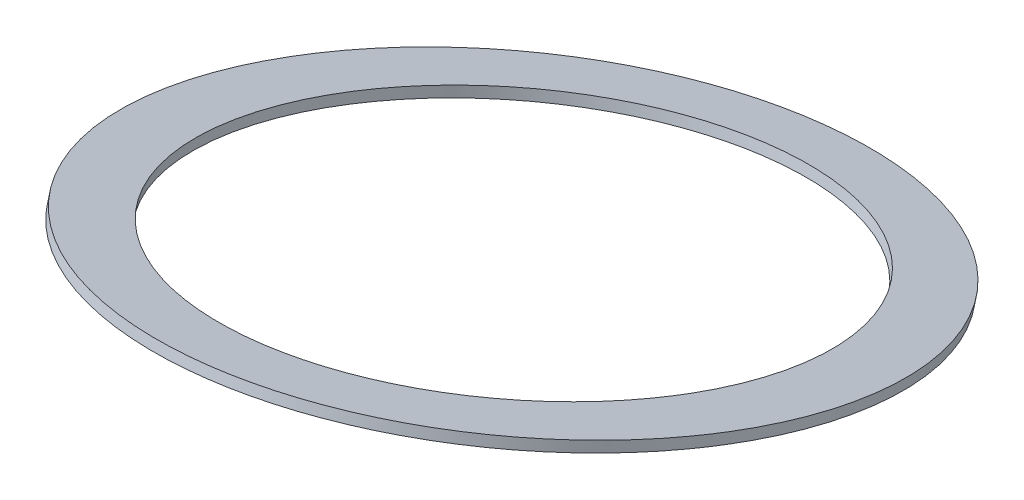
SolidWorks part; units mm, degrees
ref_plane "Front Plane" through (0, 0, 0) normal (0, 0, 1) x (1, 0, 0)
ref_plane "Top Plane" through (0, 0, 0) normal (0, 1, 0) x (1, 0, 0)
ref_plane "Right Plane" through (0, 0, 0) normal (1, 0, 0) x (0, 0, -1)
ref_plane "Plane1" through (0, 161.1863, -43.1897) normal (0, -0.9659, 0.2588) x (-1, 0, 0)
sketch "Sketch1" plane through (0, 161.1863, -43.1897) normal (0, -0.9659, 0.2588) x (-1, 0, 0)
  spline S13 degree 3 poles (-308.7796, -501.667) (-305.3895, -516.2294) (-300.1815, -534.0441) (-292.3447, -554.8396) (-282.8694, -575.0072) (-271.5712, -594.5926) (-258.682, -612.9457) (-246.5343, -627.2019) (-235.9115, -637.9156) (-227.4327, -645.612) (-218.5447, -652.8347) (-206.2279, -661.7414) (-193.1609, -669.5652) (-179.3027, -676.2043) (-164.8603, -682.0078) (-146.416, -687.367) (-127.4149, -690.2028) (-111.8465, -690.8754) (-96.2126, -690.4378) (-80.9326, -688.3858) (-65.9353, -684.7912) (-54.8125, -681.3144) (-43.956, -677.1091) (-30.0275, -670.6515) (-13.5123, -661.0389) (4.9444, -647.1509) (21.4597, -631.6127) (33.8344, -617.3625) (42.9246, -605.235) (51.3654, -592.8146) (60.8018, -576.7155) (70.4565, -556.5557) (78.5124, -535.5547) (84.8501, -514.2741) (89.5995, -492.645) (92.7963, -470.6842) (94.4358, -448.3937) (94.505, -426.3064) (93.0473, -404.3134) (90.5462, -386.075) (87.7522, -371.5422) (85.2411, -360.6433) (82.3338, -349.8672) (77.947, -335.7349) (71.4945, -318.4762) (62.1542, -298.4385) (52.9567, -282.3221) (44.6764, -269.8123) (35.7265, -257.5554) (23.5647, -243.1723) (9.9985, -230.0494) (-1.7516, -220.3943) (-11.081, -213.5726) (-20.764, -207.3285) (-34.1087, -199.8212) (-51.5992, -191.9946) (-74.1564, -185.3035) (-97.0357, -181.8392) (-116.3973, -181.5969) (-132.0466, -183.0734) (-147.3551, -185.6149) (-162.2423, -189.6888) (-176.7058, -195.236) (-190.8392, -201.7427) (-204.0822, -209.4347) (-216.5717, -218.2294) (-225.5682, -225.3634) (-234.1746, -232.998) (-244.9746, -243.6592) (-254.8758, -255.0505) (-263.9282, -267.0993) (-270.3215, -276.4853) (-276.2604, -286.1071) (-283.5646, -299.1803) (-291.6114, -315.9905) (-298.2903, -333.3741) (-302.8488, -347.6534) (-306.8399, -362.0166) (-310.7993, -380.1044) (-313.9742, -402.0322) (-315.6031, -424.1789) (-315.6666, -446.5815) (-314.164, -468.7454) (-311.6142, -487.0891) (-308.7796, -501.667) (-305.3895, -516.2294) (-300.1815, -534.0441) knots -0.03125 -0.015625 -0.007812 0 0.015625 0.03125 0.046875 0.0625 0.078125 0.09375 0.101562 0.109375 0.117188 0.125 0.140625 0.148438 0.15625 0.171875 0.1875 0.195312 0.203125 0.21875 0.226562 0.234375 0.242188 0.25 0.265625 0.28125 0.296875 0.3125 0.320312 0.328125 0.34375 0.359375 0.375 0.390625 0.40625 0.421875 0.4375 0.453125 0.46875 0.484375 0.492188 0.5 0.507812 0.515625 0.53125 0.546875 0.5625 0.570312 0.578125 0.59375 0.609375 0.617188 0.625 0.632812 0.640625 0.65625 0.671875 0.6875 0.703125 0.710938 0.71875 0.734375 0.742188 0.75 0.765625 0.773438 0.78125 0.789062 0.796875 0.8125 0.820312 0.828125 0.835938 0.84375 0.859375 0.875 0.882812 0.890625 0.90625 0.921875 0.9375 0.953125 0.96875 0.984375 0.992188 1 1.015625 1.03125 1.046875 only from (-306.1723, -512.5629) to (-306.1723, -512.5629)
  spline S15 degree 3 poles (-268.9539, -489.8575) (-266.1768, -502.1049) (-261.9041, -517.0626) (-255.4767, -534.4775) (-247.7228, -551.307) (-238.513, -567.5794) (-228.0557, -582.7559) (-218.2617, -594.4759) (-209.7442, -603.2444) (-202.9754, -609.5201) (-195.897, -615.4009) (-186.1339, -622.6255) (-175.8352, -628.9462) (-164.9813, -634.296) (-153.7061, -638.9721) (-139.3647, -643.2999) (-121.7328, -646.1129) (-103.4921, -646.4079) (-88.6691, -644.5187) (-76.9903, -641.7922) (-68.2974, -639.1235) (-59.7796, -635.8682) (-48.8013, -630.8292) (-35.6916, -623.2569) (-20.8991, -612.1841) (-7.5378, -599.6658) (2.5715, -588.0663) (10.0337, -578.1433) (16.9879, -567.946) (24.8108, -554.6557) (32.8727, -537.9052) (39.6339, -520.3915) (44.9869, -502.5808) (49.0303, -484.4132) (51.3217, -469.0137) (52.5085, -456.5179) (53.2505, -444.0571) (53.3643, -428.5306) (52.2193, -409.9898) (50.1902, -394.6147) (47.9062, -382.3742) (45.1612, -370.1415) (40.9271, -355.1906) (34.58, -337.853) (26.9356, -321.1249) (19.4338, -307.7253) (12.7025, -297.358) (5.4524, -287.2358) (-4.3529, -275.411) (-15.2186, -264.6827) (-24.5759, -256.8236) (-34.4432, -249.4412) (-47.3816, -241.4352) (-63.805, -233.8713) (-81.3397, -228.4704) (-99.0428, -225.6154) (-114.0258, -225.3011) (-126.1544, -226.356) (-138.0367, -228.2503) (-152.5382, -232.1245) (-169.497, -239.2065) (-182.6423, -246.7867) (-192.6273, -253.7806) (-199.8638, -259.4946) (-206.8005, -265.6252) (-215.5511, -274.2331) (-223.6344, -283.4996) (-231.0736, -293.3697) (-238.1056, -303.6613) (-245.9708, -317.0223) (-254.027, -333.769) (-259.6409, -348.2901) (-263.4845, -360.2392) (-266.8551, -372.2573) (-270.2236, -387.4433) (-272.9551, -405.8973) (-274.3952, -424.5869) (-274.5214, -443.4675) (-273.339, -462.1373) (-271.27, -477.5887) (-268.9539, -489.8575) (-266.1768, -502.1049) (-261.9041, -517.0626) knots -0.03125 -0.015625 -0.007812 0 0.015625 0.03125 0.046875 0.0625 0.078125 0.09375 0.101562 0.109375 0.117188 0.125 0.140625 0.148438 0.15625 0.171875 0.1875 0.203125 0.21875 0.226562 0.234375 0.242188 0.25 0.265625 0.28125 0.296875 0.3125 0.320312 0.328125 0.34375 0.359375 0.375 0.390625 0.40625 0.421875 0.429688 0.4375 0.453125 0.46875 0.484375 0.492188 0.5 0.515625 0.53125 0.546875 0.5625 0.570312 0.578125 0.59375 0.609375 0.617188 0.625 0.640625 0.65625 0.671875 0.6875 0.703125 0.710938 0.71875 0.734375 0.75 0.765625 0.773438 0.78125 0.789062 0.796875 0.8125 0.820312 0.828125 0.84375 0.859375 0.875 0.882812 0.890625 0.90625 0.921875 0.9375 0.953125 0.96875 0.984375 0.992188 1 1.015625 1.03125 1.046875 only from (-266.8176, -499.0196) to (-266.8176, -499.0196)
extrude "Boss-Extrude1" add sketch "Sketch1" along normal blind 7
